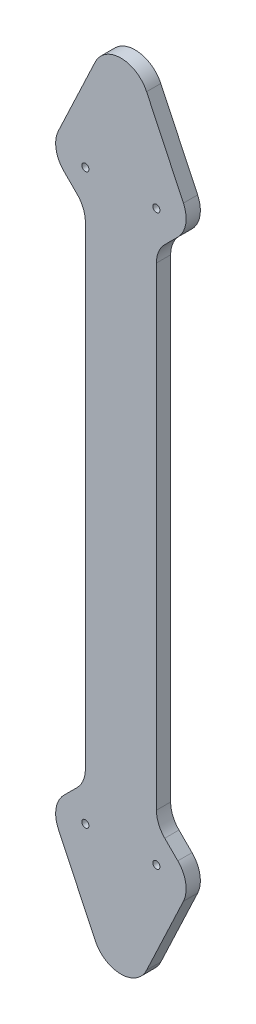
SolidWorks part; units mm, degrees
material "AISI 1045 Steel, cold drawn"
ref_plane "Front Plane" through (0, 0, 0) normal (0, 0, 1) x (1, 0, 0)
ref_plane "Top Plane" through (0, 0, 0) normal (0, 1, 0) x (1, 0, 0)
ref_plane "Right Plane" through (0, 0, 0) normal (1, 0, 0) x (0, 0, -1)
sketch "Sketch1" plane through (0, 0, 0) normal (0, 0, 1) x (1, 0, 0)
  line L0 (-3.6178, 53.5314) -> (-8.7996, 42.545)
  line L1 (-8.0103, 38.0103) -> (-6.1716, 36.1716)
  line L2 (-5, 33.3431) -> (-5, -33.3431)
  line L3 (-5, 0) -> (0, 0) construction
  line L4 (0, 0) -> (0, 61.2017) construction
  line L5 (5, 33.3431) -> (5, -33.3431)
  line L6 (8.0103, 38.0103) -> (6.1716, 36.1716)
  line L7 (3.6178, 53.5314) -> (8.7996, 42.545)
  line L8 (-8.0103, -38.0103) -> (-6.1716, -36.1716)
  line L9 (8.0103, -38.0103) -> (6.1716, -36.1716)
  line L10 (3.6178, -53.5314) -> (8.7996, -42.545)
  line L11 (-3.6178, -53.5314) -> (-8.7996, -42.545)
  line L12 (-10, 40) -> (10, 40) construction
  arc A0 (5, 33.3431) -> (6.1716, 36.1716) centre (9, 33.3431) cw
  arc A1 (-6.1716, 36.1716) -> (-5, 33.3431) centre (-9, 33.3431) cw
  arc A2 (6.1716, -36.1716) -> (5, -33.3431) centre (9, -33.3431) cw
  arc A3 (-6.1716, -36.1716) -> (-5, -33.3431) centre (-9, -33.3431) ccw
  arc A4 (8.0103, 38.0103) -> (8.7996, 42.545) centre (5.1818, 40.8387) ccw
  arc A5 (-8.7996, 42.545) -> (-8.0103, 38.0103) centre (-5.1818, 40.8387) ccw
  arc A6 (8.0103, -38.0103) -> (8.7996, -42.545) centre (5.1818, -40.8387) cw
  arc A7 (-8.0103, -38.0103) -> (-8.7996, -42.545) centre (-5.1818, -40.8387) ccw
  arc A8 (3.6178, -53.5314) -> (-3.6178, -53.5314) centre (0, -51.825) cw
  arc A9 (-3.6178, 53.5314) -> (3.6178, 53.5314) centre (0, 51.825) cw
  circle A10 centre (-5, 40) radius 0.5
  circle A11 centre (5, 40) radius 0.5
  circle A12 centre (5, -40) radius 0.5
  circle A13 centre (-5, -40) radius 0.5
  point P11 (5, 0)
  point P17 (5, 35)
  point P20 (-5, 35)
  point P23 (5, -35)
  point P26 (-5, -35)
  point P29 (10, 40)
  point P32 (-10, 40)
  point P35 (10, -40)
  point P38 (-10, -40)
  point P41 (0, -61.2017)
  point P45 (0, 55.825)
  point P46 (0, -55.825)
  point P48 (-5, 40)
  point P50 (5, 40)
  point P52 (5, -40)
  point P53 (-5, -40)
  dimension "D6" = 4
  dimension "D7" = 5
  dimension "D8" = 1
  dimension "D1" = 40
  dimension "D2" = 111.65
  dimension "D3" = 10
  dimension "D4" = 5
  dimension "D5" = 35
extrude "Boss-Extrude1" add sketch "Sketch1" along normal blind 2
